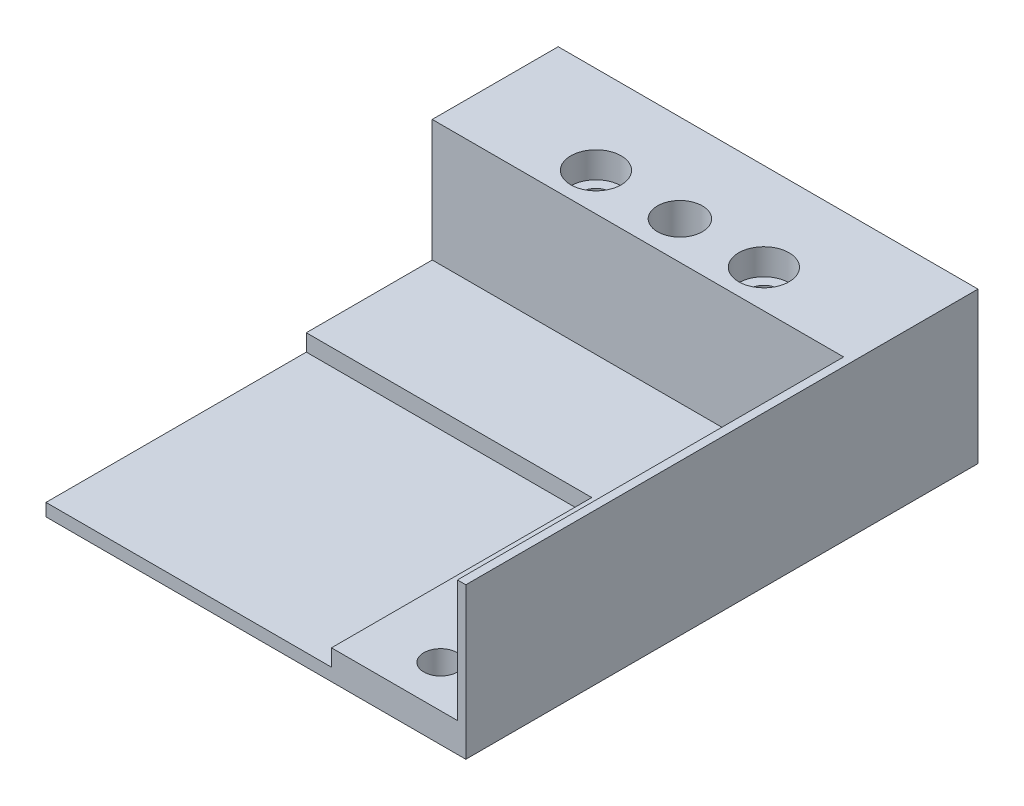
SolidWorks part; units mm, degrees
other "Markup1"
sketch "Sketch5" plane through (0, 18, 0) normal (-0.806, 0.0775, 0.5868) x (0.5918, 0.1268, 0.7961)
other "Markup2"
sketch "Sketch6" plane through (0, 18, 0) normal (-0.8829, 0.0686, 0.4646) x (0.4687, 0.0665, 0.8808)
ref_plane "Front Plane" through (0, 0, 0) normal (0, 0, 1) x (1, 0, 0)
ref_plane "Top Plane" through (0, 0, 0) normal (0, 1, 0) x (1, 0, 0)
ref_plane "Right Plane" through (0, 0, 0) normal (1, 0, 0) x (0, 0, -1)
sketch "OutlineSketch2" plane through (0, 0, 0) normal (0, 1, 0) x (1, 0, 0)
  line L1 (0, 0) -> (50, 0)
  line L2 (0, 0) -> (0, 61)
  line L3 (0, 61) -> (50, 61)
  line L4 (50, 0) -> (50, 61)
  circle A0 centre (42, 5) radius 2
  dimension "D5" = 4
  dimension "D1" = 5
  dimension "D2" = 8
  dimension "D3" = 56
  dimension "D4" = 50
extrude "OutlineBoss-Extrude1" add sketch "OutlineSketch2" along normal blind 18
sketch "BuildPlateCutoutSketch1" plane through (0, 18, 0) normal (0, 1, 0) x (1, 0, 0)
  line L1 (0, 0) -> (49, 0)
  line L2 (0, 0) -> (0, 46)
  line L3 (0, 46) -> (49, 46)
  line L4 (49, 0) -> (49, 46)
  dimension "D1" = 7
  dimension "D2" = 41
extrude "BuildPlateCutoutCut-Extrude7" cut sketch "BuildPlateCutoutSketch1" against normal blind 14.5
sketch "HeatMatCutSketch3" plane through (0, 3.5, 0) normal (0, 1, 0) x (1, 0, 0)
  line L0 (0, 0) -> (49, 0) construction
  line L1 (0, 0) -> (34, 0)
  line L2 (0, 0) -> (0, 31)
  line L3 (0, 31) -> (34, 31)
  line L4 (34, 0) -> (34, 31)
  line L5 (0, 46) -> (0, 0) construction
  line L6 (49, 46) -> (0, 46) construction
  line L7 (49, 0) -> (49, 46) construction
  dimension "D1" = 15
  dimension "D2" = 15
extrude "HeatMatCut-Extrude8" cut sketch "HeatMatCutSketch3" against normal blind 2
sketch "Sketch1" plane through (0, 18, 0) normal (0, 1, 0) x (1, 0, 0)
  line L0 (50, 0) -> (50, 61) construction
  line L2 (49, 46) -> (0, 46) construction
  circle A0 centre (35, 50.5) radius 1.75
  circle A1 centre (25, 50.5) radius 2.675
  circle A2 centre (15, 50.5) radius 1.75
  dimension "D1" = 3.5
  dimension "D2" = 5.35
  dimension "D3" = 20
  dimension "D4" = 10
  dimension "D5" = 25
  dimension "D6" = 4.5
extrude "ZEndStopSwitchMountHolesCut-Extrude1" cut sketch "Sketch1" against normal through all
sketch "Sketch3" plane through (0, 18, 0) normal (0, 1, 0) x (1, 0, 0)
  circle A0 centre (35, 50.5) radius 3
  circle A1 centre (15, 50.5) radius 3
  dimension "D1" = 6
extrude "ZEndStopSwitchMountBoreHolesCut-Extrude2" cut sketch "Sketch3" against normal blind 3.1
sketch "Sketch4" plane through (0, 0, 0) normal (0, -1, 0) x (1, 0, 0)
  circle A0 centre (25, -50.5) radius 4.125
  dimension "D1" = 8.25
extrude "ZEndStopSwitchConningTowertBoreCut-Extrude1" cut sketch "Sketch4" against normal blind 7.5
equation "\"BuildPlateStandoffHolesDistanceFromLeftOrRightSide\"= 7mm"
equation "\"BuildPlateStandoffHolesDistanceFromBackSide\"= 41mm"
equation "\"BedSpringHoleSize\"= \"M4HoleDiameter\""
equation "\"D5@OutlineSketch2\" = \"BedSpringHoleSize\""
equation "\"D1@OutlineBoss-Extrude1\" = \"BuildPlateZEndstopDepth\""
equation "\"BuildPlateStandoffHolesDistanceFromFront\"= 7mm"
equation "\"M4HoleDiameter\"= 4mm"
equation "\"D1@OutlineSketch2\"=\"RightedgeSize\"+ \"BedSpringHoleSize\""
equation "\"D2@OutlineSketch2\"=  \"BuildPlateStandoffHolesDistanceFromFront\" + \"RightedgeSize\""
equation "\"D3@OutlineSketch2\" = \"BuildPlateStandoffHolesDistanceFromBackSide\" + \"BackEdgeSize\""
equation "\"RightedgeSize\"= 1mm"
equation "\"MicroSwitchExtraMountingHeight\"= 2mm"
equation "\"ZEndStopSwitchDepth\"= 21mm"
equation "\"BuildPlateZEndstopDepth\"= \"ZEndStopTotalPlungerHeight\""
equation "\"BackEdgeSize\"= \"ZEndStopSwitchDepth\" - \"ZEndStopSwitchConningTowerDiameter\" + 2mm"
equation "\"M2HeatInsertHoleDiameter\"= 3mm'Spec"
equation "\"M2HeatInsertHoleDepth\"= 3.1mm'Spec"
equation "\"BuildPlateEndStopHolderWidth\"= 50mm"
equation "\"D4@OutlineSketch2\"=\"BuildPlateEndStopHolderWidth\""
equation "\"BuildPlateDepth\"= 8mm'Spec"
equation "\"D1@BuildPlateCutoutSketch1\" = \"BuildPlateStandoffHolesDistanceFromLeftOrRightSide\""
equation "\"D2@BuildPlateCutoutSketch1\" = \"BuildPlateStandoffHolesDistanceFromBackSide\""
equation "\"D1@BuildPlateCutoutCut-Extrude7\"=\"BuildPlateDepth\" + \"MagneticPlateDepth\" + \"GlassBuildPlateDepth\""
equation "\"BallJointDiameter\"= 1in"
equation "\"HeatMatBuildPlateBorderSize\"=15"
equation "\"D1@HeatMatCutSketch3\"=\"HeatMatBuildPlateBorderSize\""
equation "\"D2@HeatMatCutSketch3\"=\"HeatMatBuildPlateBorderSize\""
equation "\"D1@BallJointCutoutSketch4\"=\"BallJointDiameter\" + 10mm"
equation "\"ZEndStopSwitchHeight\"= 8mm"
equation "\"D5@Sketch1\"=\"BuildPlateEndStopHolderWidth\" /2"
equation "\"ZEndStopDistanceBetweenMountingHoles\"=20"
equation "\"D3@Sketch1\"=\"ZEndStopDistanceBetweenMountingHoles\""
equation "\"D4@Sketch1\"=\"ZEndStopDistanceBetweenMountingHoles\"/2"
equation "\"ZEndStopSwitchConningTowerDiameter\"= 8mm"
equation "\"ZEndStopSwitchConningTowerHeight\"= 7mm"
equation "\"D6@Sketch1\"=\"ZEndStopSwitchPlungerDiameter\"/2 + 2mm"
equation "\"ZEndStopSwitchPlungerDiameter\"=5"
equation "\"D2@Sketch1\"=\"ZEndStopSwitchPlungerDiameter\" + .35mm"
equation "\"D1@Sketch4\"=\"ZEndStopSwitchConningTowerDiameter\" + .25mm"
equation "\"D1@ZEndStopSwitchConningTowertBoreCut-Extrude1\" = \"ZEndStopSwitchConningTowerHeight\" + .5mm"
equation "\"M3ButtonHeadHeight\"=3.1"
equation "\"D1@ZEndStopSwitchMountBoreHolesCut-Extrude2\"=\"M3ButtonHeadHeight\""
equation "\"ZEndStopPlungerHeight\"= 12mm"
equation "\"MagneticPlateDepth\"= 2.5mm"
equation "\"GlassBuildPlateDepth\"= 4mm'Spec"
equation "\"ZEndStopTotalPlungerHeight\"= \"ZEndStopSwitchConningTowerHeight\" + \"ZEndStopPlungerHeight\" - 1mm'Equals 18mm. Minus 1mm for a little protrusion"
